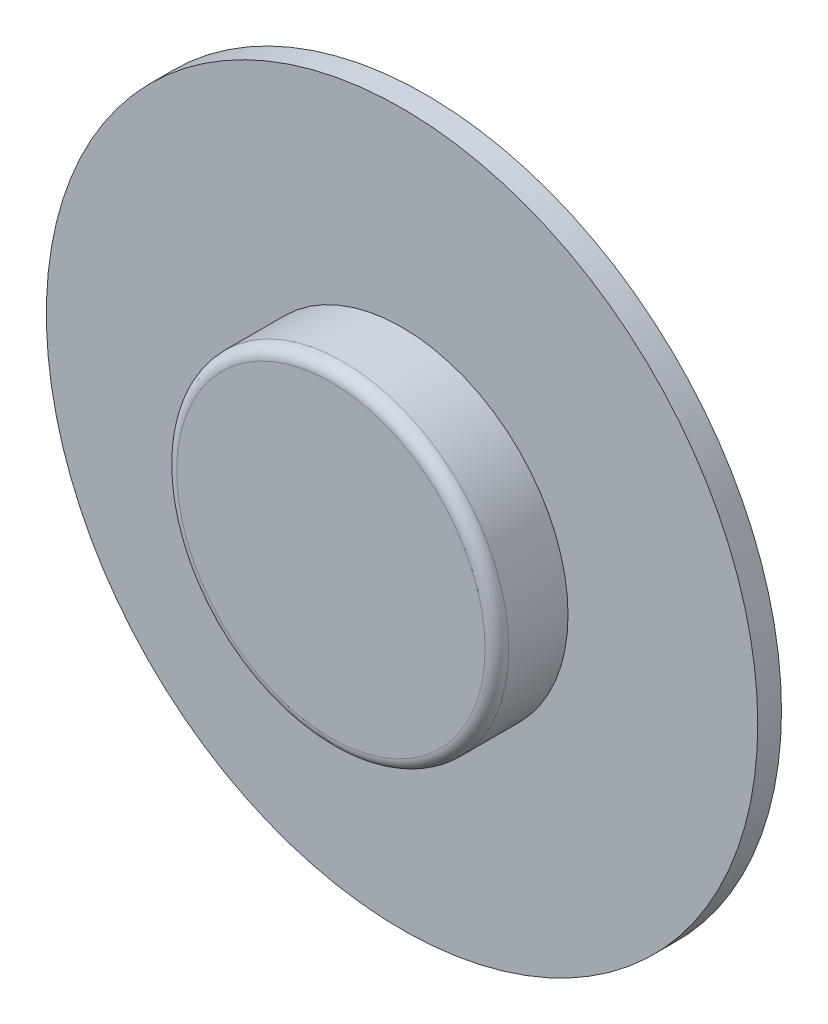
SolidWorks part; units mm, degrees
ref_plane "Plan de face" through (0, 0, 0) normal (0, 0, 1) x (1, 0, 0)
ref_plane "Plan de dessus" through (0, 0, 0) normal (0, 1, 0) x (1, 0, 0)
ref_plane "Plan de droite" through (0, 0, 0) normal (1, 0, 0) x (0, 0, -1)
sketch "Esquisse1" plane through (0, 0, 0) normal (0, 0, 1) x (1, 0, 0)
  circle A0 centre (0, 0) radius 15
  dimension "D1" = 30
extrude "Boss.-Extru.1" add sketch "Esquisse1" along normal blind 1
sketch "Esquisse2" plane through (0, 0, 1) normal (0, 0, 1) x (1, 0, 0)
  circle A0 centre (0, 0) radius 7
  dimension "D1" = 14
extrude "Boss.-Extru.2" add sketch "Esquisse2" along normal blind 3
fillet "Congé1" radius 0.5 1 edges at (7, 0, 4)
sketch "Esquisse3" plane through (0, 0, 0) normal (0, 0, -1) x (-1, 0, 0)
  circle A0 centre (0, 0) radius 4
  dimension "D1" = 8
extrude "Boss.-Extru.3" add sketch "Esquisse3" along normal blind 5
